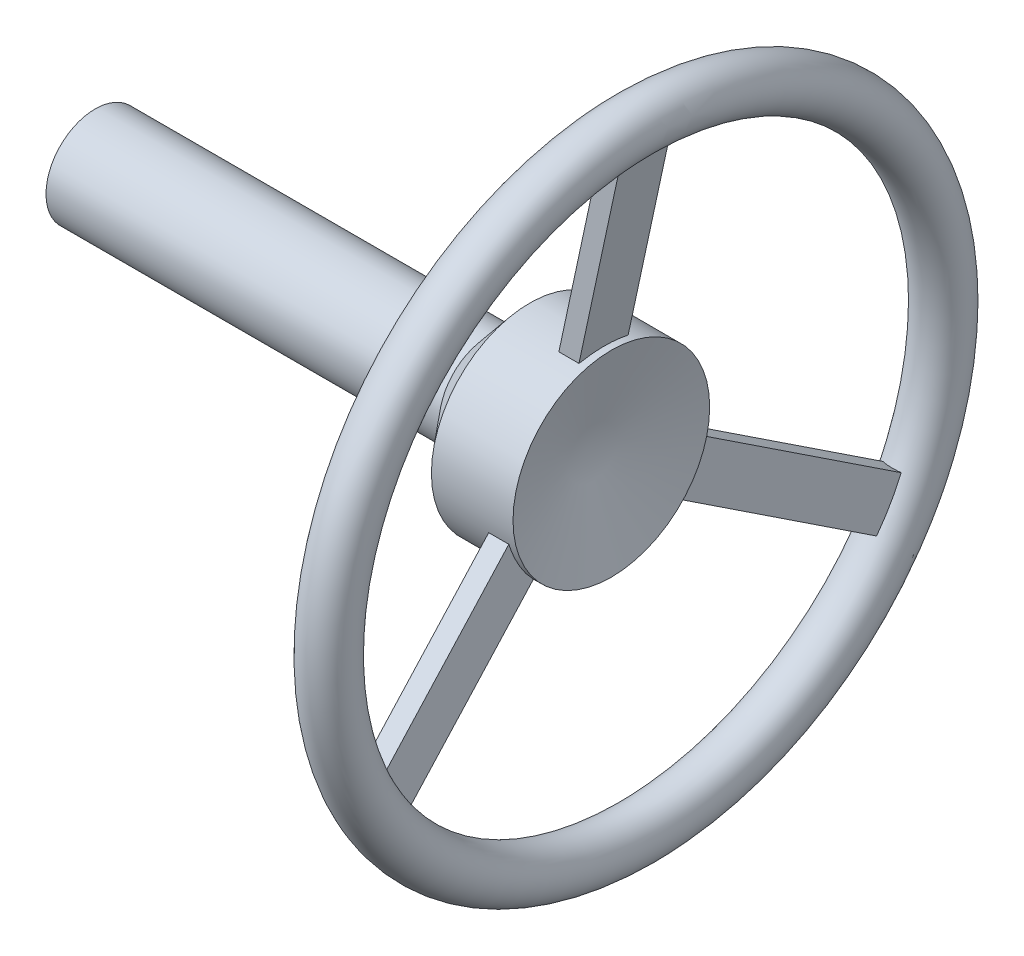
SolidWorks part; units mm, degrees
ref_plane "Front Plane" through (0, 0, 0) normal (0, 0, 1) x (1, 0, 0)
ref_plane "Top Plane" through (0, 0, 0) normal (0, 1, 0) x (1, 0, 0)
ref_plane "Right Plane" through (0, 0, 0) normal (1, 0, 0) x (0, 0, -1)
sketch "Sketch1" plane through (0, 0, 0) normal (0, 0, 1) x (1, 0, 0)
  line L0 (-81.8696, 0) -> (35.7352, 0) construction
  line L1 (49.9707, 0) -> (52.4955, 10)
  line L2 (52.4955, 10) -> (44.1955, 10)
  line L3 (44.1955, 10) -> (40, 5)
  line L4 (40, 5) -> (0, 5)
  line L5 (0, 5) -> (0, 0)
  line L6 (0, 0) -> (49.9707, 0)
  point P5 (-81.8696, 0)
  point P10 (9.6371, 0)
  point P11 (0, 0)
  point P12 (0, 0)
  dimension "D1" = 40
  dimension "D2" = 130
  dimension "D3" = 8.3
  dimension "D4" = 5
  dimension "D5" = 10
  dimension "D6" = 75.83
revolve "Revolve1" add sketch "Sketch1" angle 360 about L0
sketch "Sketch2" plane through (0, 0, 0) normal (0, 0, 1) x (1, 0, 0)
  line L1 (0, 0) -> (73.838, 0) construction
  circle A0 centre (55, 31.25) radius 2.5
  dimension "D1" = 5
  dimension "D2" = 55
  dimension "D3" = 31.25
revolve "Revolve2" add sketch "Sketch2" angle 360 about L1
sketch "Sketch3" plane through (0, 0, 0) normal (0, 0, 1) x (1, 0, 0)
  line L0 (51.6, 9.2) -> (49.5544, 9.2)
  line L1 (49.5544, 9.2) -> (53.9744, 29.7797)
  line L2 (53.9744, 29.7797) -> (56.02, 29.7797)
  line L3 (56.02, 29.7797) -> (51.6, 9.2)
  line L4 (52.5, 31.25) -> (52.5, -31.25) construction
  point P2 (50.5772, 9.2)
  dimension "D1" = 2
  dimension "D2" = 9.2
  dimension "D3" = 0.9
  dimension "D4" = 4.42
extrude "Boss-Extrude1" add sketch "Sketch3" along normal mid plane 5
pattern_circular "CirPattern1" count 3 over 360 about axis through (0, 0, 0) along (1, 0, 0) of "Boss-Extrude1"
